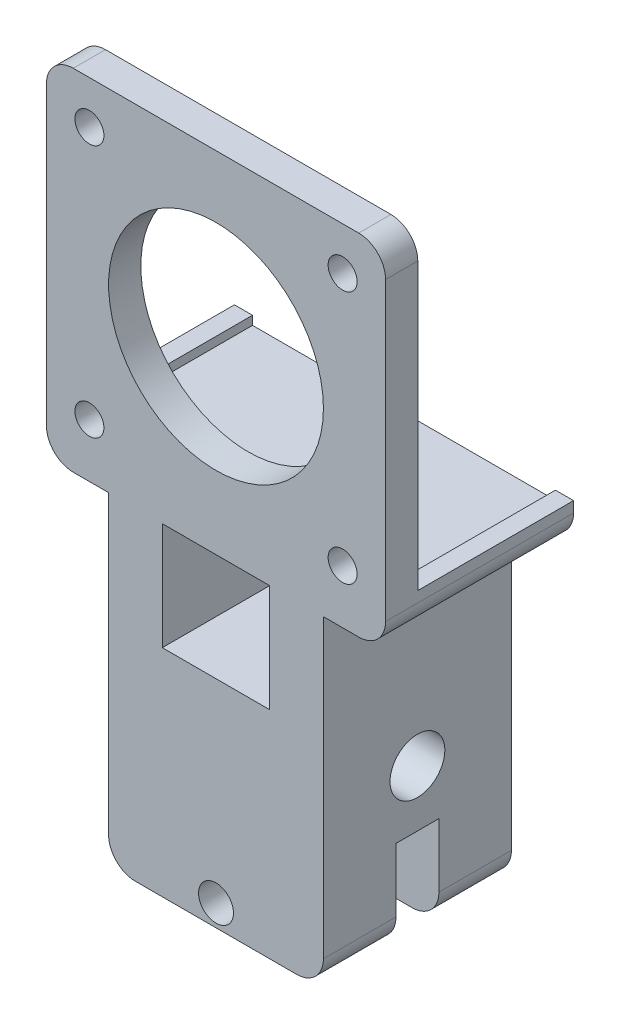
SolidWorks part; units mm, degrees
ref_plane "Alzado" through (0, 0, 0) normal (0, 0, 1) x (1, 0, 0)
ref_plane "Planta" through (0, 0, 0) normal (0, 1, 0) x (1, 0, 0)
ref_plane "Vista lateral" through (0, 0, 0) normal (1, 0, 0) x (0, 0, -1)
sketch "Croquis1" plane through (0, 0, 0) normal (0, 0, 1) x (1, 0, 0)
  line L1 (5, 0) -> (35, 0)
  line L2 (0, 5) -> (0, 40.17)
  line L3 (0, 40.17) -> (40, 40.17)
  line L4 (40, 5) -> (40, 40.17)
  line L5 (20, 0) -> (20, 4) construction
  line L6 (10, 60.17) -> (30, 60.17)
  line L7 (10, 60.17) -> (10, 40.17)
  line L8 (10, 40.17) -> (30, 40.17)
  line L9 (30, 60.17) -> (30, 40.17)
  line L10 (10, 60.17) -> (30, 40.17) construction
  line L11 (10, 40.17) -> (30, 60.17) construction
  line L12 (0, 40.17) -> (40, 40.17)
  line L13 (0, 40.17) -> (0, 60.17)
  line L14 (5, 65.17) -> (35, 65.17)
  line L15 (40, 40.17) -> (40, 60.17)
  circle A1 centre (20, 4) radius 3.25
  arc A2 (5, 0) -> (0, 5) centre (5, 5) cw
  arc A3 (35, 0) -> (40, 5) centre (35, 5) ccw
  arc A4 (35, 65.17) -> (40, 60.17) centre (35, 60.17) cw
  arc A5 (0, 60.17) -> (5, 65.17) centre (5, 60.17) cw
  point P7 (20, 50.17)
  point P21 (0, 0)
  point P24 (40, 0)
  point P29 (0, 65.17)
  dimension "D5" = 6.5
  dimension "D10" = 5
  dimension "D1" = 40
  dimension "D2" = 40.17
  dimension "D3" = 10
  dimension "D4" = 20
  dimension "D6" = 20
  dimension "D9" = 25
  dimension "D11" = 4
extrude "Saliente-Extruir1" add sketch "Croquis1" along normal blind 35
sketch "Croquis3" plane through (0, 0, 0) normal (-1, 0, 0) x (0, 0, 1)
  line L0 (17.5, 0) -> (17.5, 16.86) construction
  line L1 (35, 0) -> (0, 0) construction
  line L2 (17.5, 0) -> (17.5, 27.36) construction
  line L3 (13.5, 0) -> (21.5, 0)
  line L4 (13.5, 0) -> (13.5, 16.86)
  line L5 (13.5, 16.86) -> (21.5, 16.86)
  line L6 (21.5, 0) -> (21.5, 16.86)
  line L7 (13.5, 0) -> (21.5, 16.86) construction
  line L8 (13.5, 16.86) -> (21.5, 0) construction
  circle A4 centre (17.5, 27.36) radius 5.1
  point P4 (17.5, 8.43)
  point P17 (35, 0)
  point P24 (0, 65.17)
  dimension "D3" = 0
  dimension "D4" = 10.2
  dimension "D1" = 8
  dimension "D2" = 16.86
  dimension "D5" = 27.36
extrude "Cortar-Extruir2" cut sketch "Croquis3" against normal through all
sketch "Croquis4" plane through (0, 0, 0) normal (-1, 0, 0) x (0, 0, 1)
  circle A0 centre (17.5, 27.36) radius 11
  dimension "D1" = 22
extrude "Cortar-Extruir3" cut sketch "Croquis4" against normal blind 3.5
sketch "Croquis5" plane through (0, 0, 35) normal (0, 0, 1) x (1, 0, 0)
  line L0 (20, 60.17) -> (20, 93.74) construction
  line L1 (10, 60.17) -> (30, 60.17) construction
  line L2 (-11.57, 120.31) -> (-11.57, 67.17)
  line L3 (-3.57, 117.31) -> (43.57, 117.31)
  line L4 (-3.57, 117.31) -> (-3.57, 70.17)
  line L5 (-3.57, 70.17) -> (43.57, 70.17)
  line L6 (43.57, 117.31) -> (43.57, 70.17)
  line L7 (-3.57, 117.31) -> (43.57, 70.17) construction
  line L8 (-3.57, 70.17) -> (43.57, 117.31) construction
  line L13 (-6.57, 62.17) -> (46.57, 62.17)
  line L14 (51.57, 120.31) -> (51.57, 67.17)
  line L15 (-6.57, 125.31) -> (46.57, 125.31)
  line L16 (-11.57, 125.31) -> (-11.57, 62.17) construction
  line L17 (-11.57, 62.17) -> (51.57, 62.17) construction
  line L18 (51.57, 125.31) -> (51.57, 62.17) construction
  line L19 (-11.57, 125.31) -> (51.57, 125.31) construction
  line L20 (30, 60.17) -> (30, 40.17) construction
  line L21 (10, 60.17) -> (30, 60.17)
  line L22 (10, 60.17) -> (10, 62.17)
  line L23 (10, 62.17) -> (30, 62.17)
  line L24 (30, 60.17) -> (30, 62.17)
  circle A0 centre (20, 93.74) radius 20
  circle A1 centre (-3.57, 117.31) radius 2.7
  circle A2 centre (43.57, 117.31) radius 2.7
  circle A3 centre (43.57, 70.17) radius 2.7
  circle A4 centre (-3.57, 70.17) radius 2.7
  arc A5 (-11.57, 67.17) -> (-6.57, 62.17) centre (-6.57, 67.17) ccw
  arc A6 (46.57, 62.17) -> (51.57, 67.17) centre (46.57, 67.17) ccw
  arc A7 (51.57, 120.31) -> (46.57, 125.31) centre (46.57, 120.31) ccw
  arc A8 (-11.57, 120.31) -> (-6.57, 125.31) centre (-6.57, 120.31) cw
  dimension "D1" = 40
  dimension "D5" = 5.4
  dimension "D9" = 5
  dimension "D2" = 47.14
  dimension "D3" = 47.14
  dimension "D4" = 10
  dimension "D6" = 8
  dimension "D7" = 2
  dimension "D8" = 2
extrude "Saliente-Extruir3" add sketch "Croquis5" against normal blind 6
sketch "Croquis8" plane through (0, 0, 29) normal (0, 0, -1) x (-1, 0, 0)
  line L0 (-10, 60.17) -> (11.57, 60.17) construction
  line L2 (6.57, 60.17) -> (-46.57, 60.17)
  line L7 (11.57, 75.9534) -> (11.57, 60.17) construction
  line L8 (11.57, 120.31) -> (11.57, 67.17) construction
  line L9 (11.57, 65.17) -> (11.57, 67.17)
  line L10 (11.57, 67.17) -> (-51.57, 67.17)
  line L11 (-51.57, 65.17) -> (-51.57, 67.17)
  arc A0 (6.57, 60.17) -> (11.57, 65.17) centre (6.57, 65.17) ccw
  arc A1 (-46.57, 60.17) -> (-51.57, 65.17) centre (-46.57, 65.17) cw
  dimension "D1" = 5
extrude "Saliente-Extruir5" add sketch "Croquis8" along normal through all and the other way through all
sketch "Croquis9" plane through (0, 0, 0) normal (0, 0, -1) x (-1, 0, 0)
  line L0 (3.57, 70.17) -> (-43.57, 117.31) construction
  line L2 (8.2, 121.94) -> (-48.2, 121.94)
  line L3 (8.2, 121.94) -> (8.2, 65.54)
  line L4 (8.2, 65.54) -> (-48.2, 65.54)
  line L5 (-48.2, 121.94) -> (-48.2, 65.54)
  line L6 (8.2, 121.94) -> (-48.2, 65.54) construction
  line L7 (8.2, 65.54) -> (-48.2, 121.94) construction
  point P4 (-20, 93.74)
  dimension "D1" = 56.4
  dimension "D2" = 56.4
extrude "Cortar-Extruir4" cut sketch "Croquis9" against normal up to surface (29 mm away) up to face at (40, 93.74, 29)
